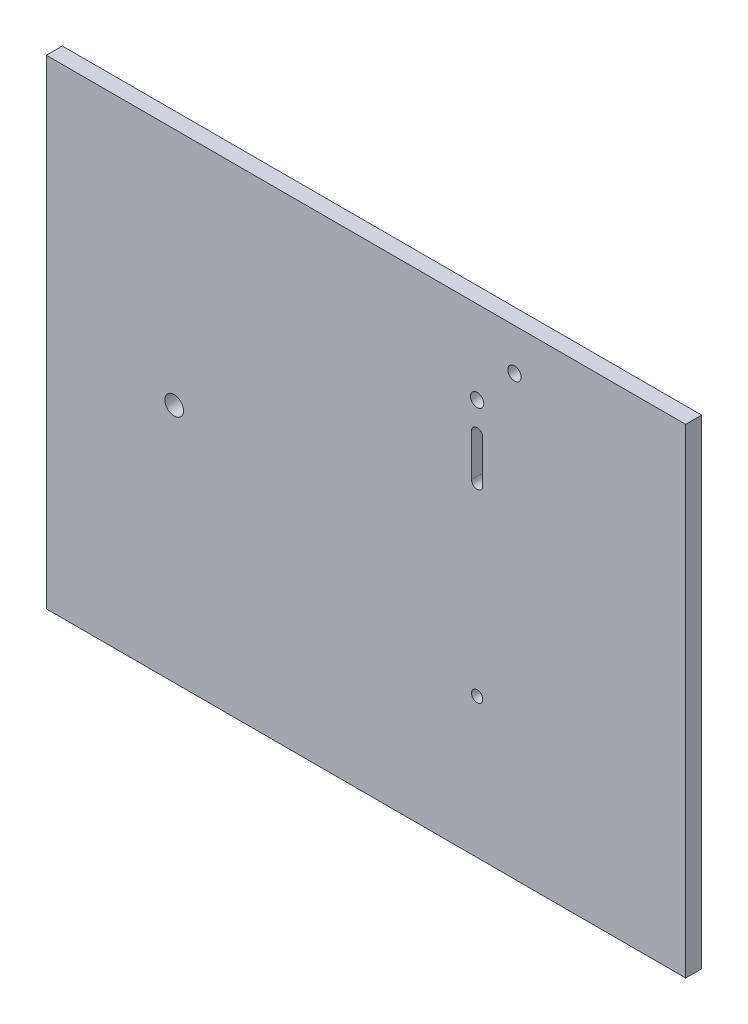
SolidWorks part; units mm, degrees
ref_plane "Front Plane" through (0, 0, 0) normal (0, 0, 1) x (1, 0, 0)
ref_plane "Top Plane" through (0, 0, 0) normal (0, 1, 0) x (1, 0, 0)
ref_plane "Right Plane" through (0, 0, 0) normal (1, 0, 0) x (0, 0, -1)
sketch "Sketch1" plane through (0, 0, 0) normal (0, 0, 1) x (1, 0, 0)
  line L0 (4, -3) -> (4, -74) construction
  line L1 (0, 0) -> (120, 0)
  line L2 (0, 0) -> (0, -90)
  line L3 (0, -90) -> (120, -90)
  line L4 (120, 0) -> (120, -90)
  line L5 (4, -3) -> (0, -3) construction
  line L6 (4, -3) -> (4, 0) construction
  line L7 (60, 0) -> (60, -90) construction
  line L8 (116, -3) -> (116, -74) construction
  circle A0 centre (4, -3) radius 1.35 construction
  circle A1 centre (4, -74) radius 1.35 construction
  circle A2 centre (116, -3) radius 1.35 construction
  circle A3 centre (116, -74) radius 1.35 construction
  dimension "D1" = 2.7
  dimension "D2" = 2.7
  dimension "D9" = 2.7
  dimension "D10" = 2.7
  dimension "D3" = 71
  dimension "D4" = 4
  dimension "D5" = 3
  dimension "D6" = 120
  dimension "D7" = 90
  dimension "D8" = 16
extrude "Boss-Extrude1" add sketch "Sketch1" along normal blind 3
fillet "Fillet1" [suppressed] radius 3
sketch "Sketch3" plane through (0, 0, 3) normal (0, 0, 1) x (1, 0, 0)
  line L0 (80.8564, -29.0907) -> (80.8564, -21.1496) construction
  line L1 (79.8064, -29.0907) -> (79.8064, -21.1496)
  line L2 (81.9064, -29.0907) -> (81.9064, -21.1496)
  circle A0 centre (24, -44.9) radius 1.75
  circle A1 centre (80.8564, -28.7626) radius 1.05 construction
  circle A2 centre (80.8564, -63.7626) radius 1.05
  arc A3 (79.8064, -29.0907) -> (81.9064, -29.0907) centre (80.8564, -29.0907) ccw
  arc A4 (81.9064, -21.1496) -> (79.8064, -21.1496) centre (80.8564, -21.1496) ccw
  point P11 (80.8564, -25.1202)
  dimension "D1" = 3.5
  dimension "D2" = 2.1
extrude "Cut-Extrude1" cut sketch "Sketch3" against normal up to surface (3 mm away) up to face at (60, -45, 0)
sketch "Sketch5" plane through (0, 0, 0) normal (0, 0, -1) x (-1, 0, 0)
  circle A0 centre (-24, -44.9) radius 3
  dimension "D1" = 6
extrude "Cut-Extrude2" [suppressed] cut sketch "Sketch5" against normal blind 0.5
sketch "Sketch7" plane through (0, 0, 3) normal (0, 0, 1) x (1, 0, 0)
  line L0 (80.8564, -20.0996) -> (80.8564, -15.5996) construction
  line L1 (80.8564, -15.5996) -> (81.03, -16.8374)
  line L2 (80.8564, -15.5996) -> (87.8704, -7.7859) construction
  arc A0 (81.9064, -21.1496) -> (79.8064, -21.1496) centre (80.8564, -21.1496) ccw construction
  circle A1 centre (80.8564, -15.5996) radius 1.25
  circle A2 centre (87.8704, -7.7859) radius 1.25
  dimension "D2" = 2.5
  dimension "D4" = 2.5
  dimension "D1" = 4.5
  dimension "D3" = 10.5
extrude "Cut-Extrude3" cut sketch "Sketch7" against normal up to surface (3 mm away) up to face at (25.75, -44.9, 0)
